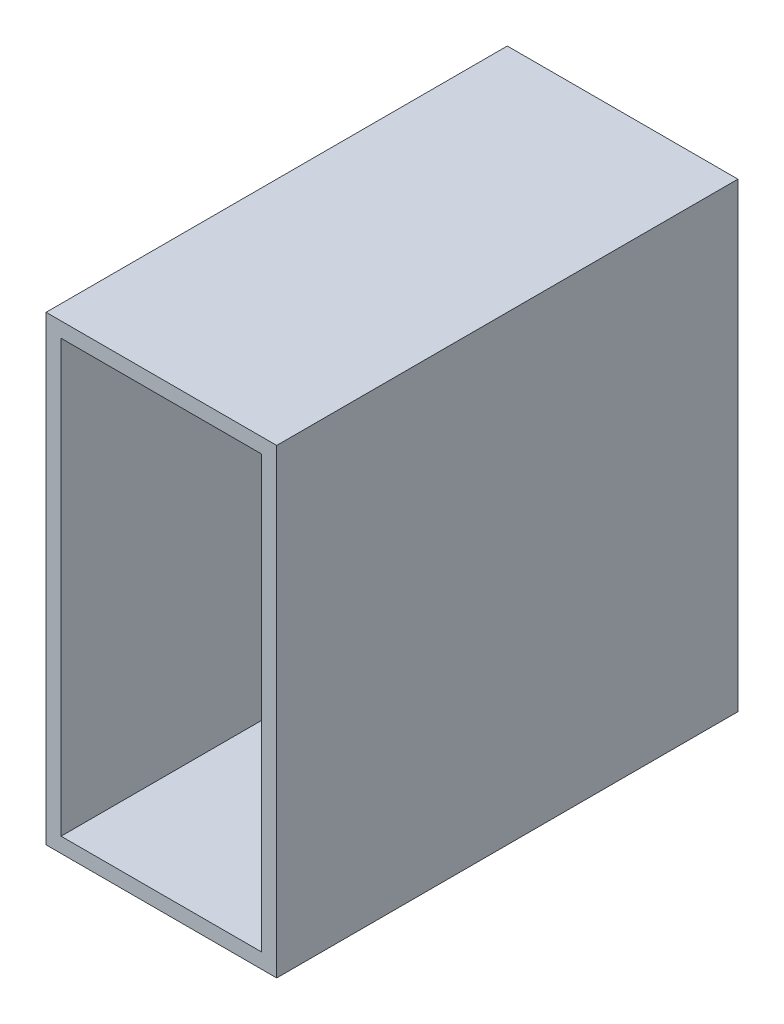
SolidWorks part; units mm, degrees
material "6061 Alloy"
ref_plane "Front Plane" through (0, 0, 0) normal (0, 0, 1) x (1, 0, 0)
ref_plane "Top Plane" through (0, 0, 0) normal (0, 1, 0) x (1, 0, 0)
ref_plane "Right Plane" through (0, 0, 0) normal (1, 0, 0) x (0, 0, -1)
sketch "Sketch1" plane through (0, 0, 0) normal (0, 0, 1) x (1, 0, 0)
  line L1 (-48.4372, -30.1994) -> (-23.0372, -30.1994)
  line L2 (-48.4372, -30.1994) -> (-48.4372, 20.6006)
  line L3 (-48.4372, 20.6006) -> (-23.0372, 20.6006)
  line L4 (-23.0372, -30.1994) -> (-23.0372, 20.6006)
  dimension "D1" = 25.4
  dimension "D2" = 50.8
extrude "Boss-Extrude1" add sketch "Sketch1" along normal blind 50.8
sketch "Sketch2" plane through (0, 0, 50.8) normal (0, 0, 1) x (1, 0, 0)
  line L0 (-48.4372, 20.6006) -> (-48.4372, -30.1994) construction
  line L1 (-46.7862, 18.9496) -> (-24.6882, 18.9496)
  line L2 (-46.7862, 18.9496) -> (-46.7862, -28.5484)
  line L3 (-46.7862, -28.5484) -> (-24.6882, -28.5484)
  line L4 (-24.6882, 18.9496) -> (-24.6882, -28.5484)
  line L5 (-46.7862, 18.9496) -> (-24.6882, -28.5484) construction
  line L6 (-46.7862, -28.5484) -> (-24.6882, 18.9496) construction
  line L7 (-23.0372, -30.1994) -> (-23.0372, 20.6006) construction
  line L8 (-23.0372, 20.6006) -> (-48.4372, 20.6006) construction
  line L9 (-48.4372, -30.1994) -> (-23.0372, -30.1994) construction
  point P0 (-35.7372, -4.7994)
  dimension "D1" = 1.651
  dimension "D2" = 1.651
  dimension "D3" = 1.651
  dimension "D4" = 1.651
extrude "Cut-Extrude1" cut sketch "Sketch2" against normal through all
